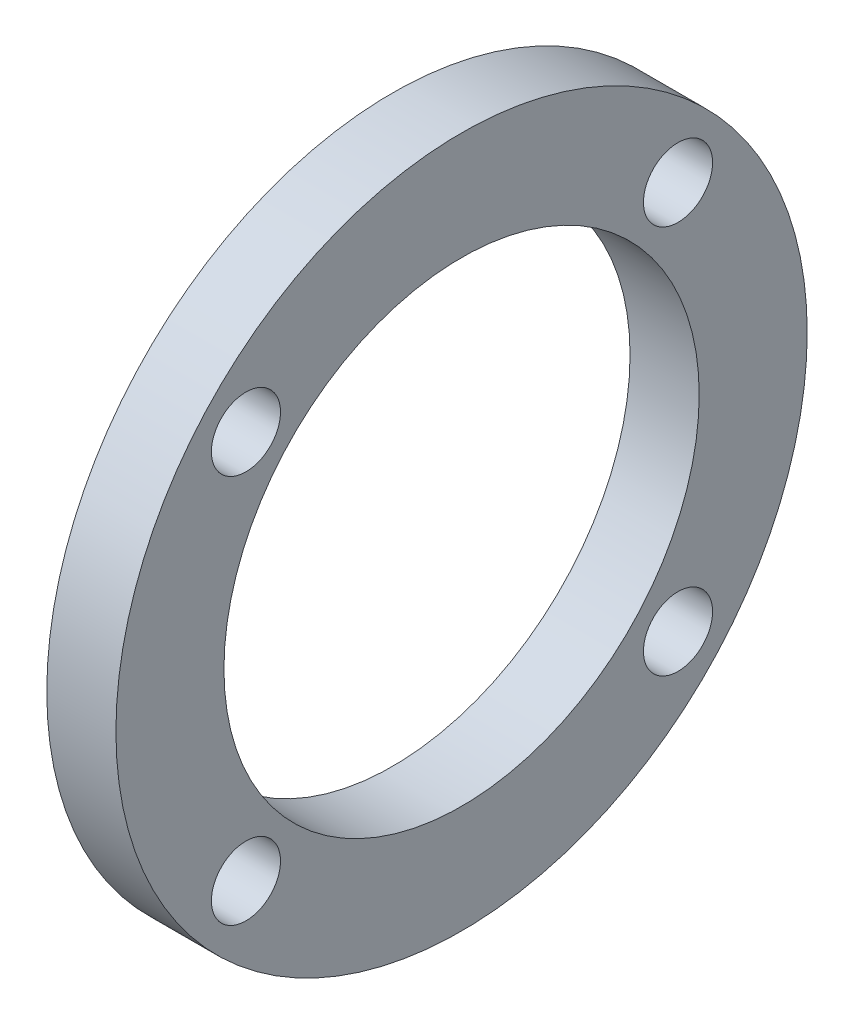
SolidWorks part; units mm, degrees
ref_plane "Front Plane" through (0, 0, 0) normal (0, 0, 1) x (1, 0, 0)
ref_plane "Top Plane" through (0, 0, 0) normal (0, 1, 0) x (1, 0, 0)
ref_plane "Right Plane" through (0, 0, 0) normal (1, 0, 0) x (0, 0, -1)
sketch "Sketch1" plane through (0, 0, 0) normal (1, 0, 0) x (0, 0, -1)
  circle A0 centre (0, 0) radius 40
  dimension "D1" = 80
extrude "Boss-Extrude1" add sketch "Sketch1" along normal blind 8
sketch "Sketch3" plane through (8, 0, 0) normal (1, 0, 0) x (0, 0, -1)
  line L0 (0, 40) -> (0, -40.8887)
  line L1 (-40, 0) -> (40, 0)
  circle A0 centre (0, 0) radius 40 construction
  circle A1 centre (-24.9542, -22.5) radius 4
  circle A2 centre (25.0458, -22.5) radius 4
  circle A3 centre (25.0458, 22.5) radius 4
  circle A4 centre (-24.9542, 22.5) radius 4
  dimension "D1" = 8
  dimension "D2" = 8
  dimension "D3" = 50
  dimension "D4" = 22.5
  dimension "D5" = 33.6
  dimension "D6" = 33.6681
extrude "Cut-Extrude1" cut sketch "Sketch3" against normal blind 8 contours A4 | A3 | A1 | A2
sketch "Sketch4" plane through (8, 0, 0) normal (1, 0, 0) x (0, 0, -1)
  circle A0 centre (0, 0) radius 27.5
  dimension "D1" = 55
extrude "Cut-Extrude2" cut sketch "Sketch4" against normal blind 8
